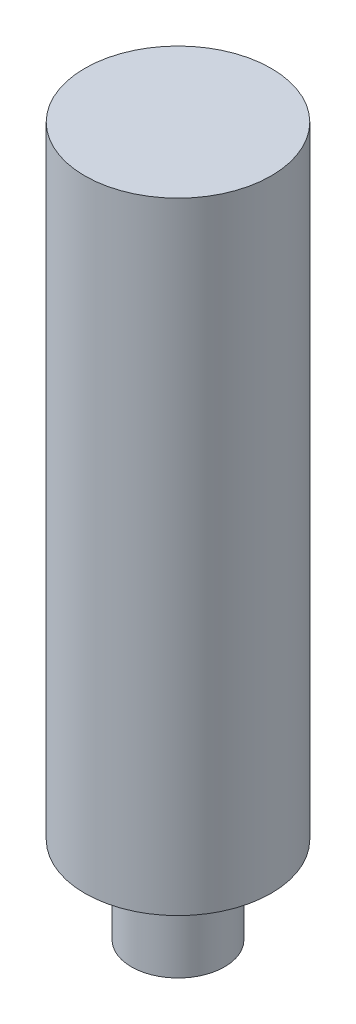
SolidWorks part; units mm, degrees
ref_plane "前基準面" through (0, 0, 0) normal (0, 0, 1) x (1, 0, 0)
ref_plane "上基準面" through (0, 0, 0) normal (0, 1, 0) x (1, 0, 0)
ref_plane "右基準面" through (0, 0, 0) normal (1, 0, 0) x (0, 0, -1)
sketch "草圖1" plane through (0, 0, 0) normal (0, 1, 0) x (1, 0, 0)
  circle A0 centre (0, 0) radius 1.5
extrude "填料-伸長1" add sketch "草圖1" along normal blind 2.8
sketch "草圖2" plane through (0, 2.8, 0) normal (0, 1, 0) x (1, 0, 0)
  circle A0 centre (0, 0) radius 3
extrude "填料-伸長2" add sketch "草圖2" along normal blind 20
